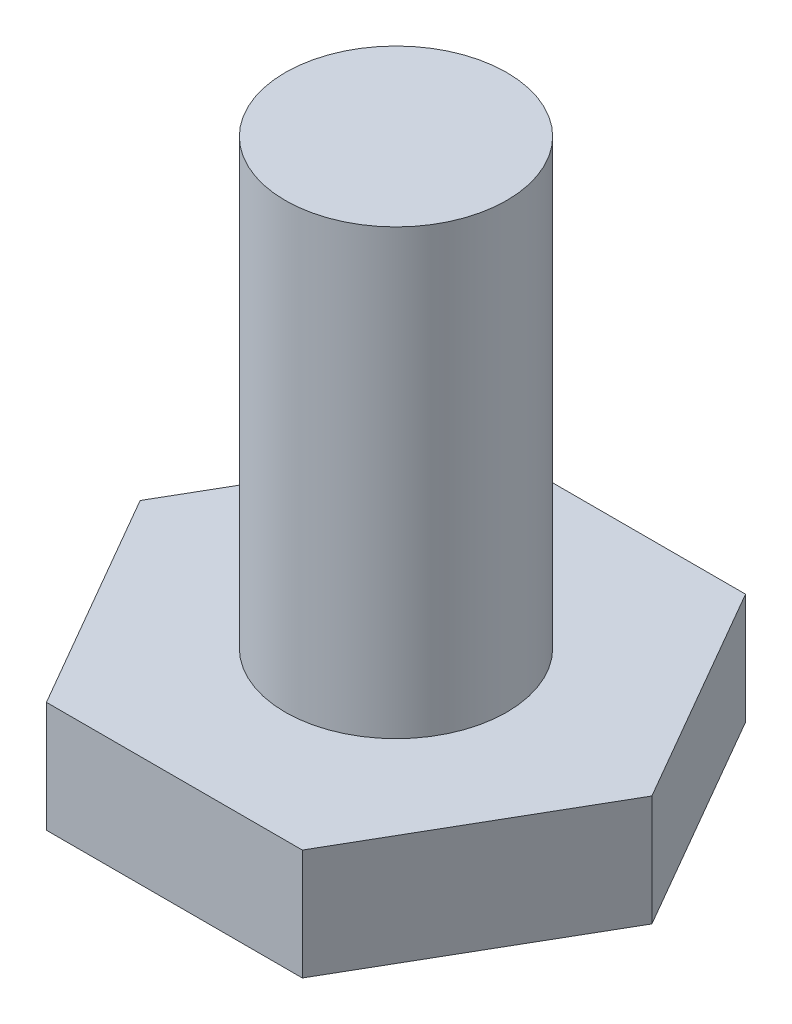
SolidWorks part; units mm, degrees
ref_plane "Front Plane" through (0, 0, 0) normal (0, 0, 1) x (1, 0, 0)
ref_plane "Top Plane" through (0, 0, 0) normal (0, 1, 0) x (1, 0, 0)
ref_plane "Right Plane" through (0, 0, 0) normal (1, 0, 0) x (0, 0, -1)
sketch "Sketch1" plane through (0, 0, 0) normal (0, 1, 0) x (1, 0, 0)
  line L1 (-2.3094, 4) -> (-4.6188, 0)
  line L2 (-4.6188, 0) -> (-2.3094, -4)
  line L3 (-2.3094, -4) -> (2.3094, -4)
  line L4 (2.3094, -4) -> (4.6188, 0)
  line L5 (4.6188, 0) -> (2.3094, 4)
  line L6 (2.3094, 4) -> (-2.3094, 4)
  circle A0 centre (0, 0) radius 4 construction
  dimension "D1" = 8
extrude "Boss-Extrude1" add sketch "Sketch1" along normal blind 2
sketch "Sketch2" plane through (0, 0, 0) normal (0, 1, 0) x (1, 0, 0)
  circle A0 centre (0, 0) radius 2
  dimension "D1" = 4
extrude "Boss-Extrude2" add sketch "Sketch2" along normal blind 10
thread "Thread1" pitch 0.7 start angle 0, offset 0, length 0, pitch 0.7, diameter 4
ref_plane "Plane1" through (-2, 10, 0) normal (0, 0, 1) x (-1, 0, 0)
sketch "Thread Profile1" plane through (-2, 10, 0) normal (0, 0, 1) x (-1, 0, 0)
  line L0 (0, 0) -> (0, 0.7) construction
  line L11 (0, 0) -> (0, 0.6125)
  line L12 (0, 0.6125) -> (-0.3789, 0.3937)
  line L13 (-0.3789, 0.3937) -> (-0.3789, 0.2187)
  line L15 (-0.3789, 0.2187) -> (0, 0)
  line L17 (-0.3789, 0.3062) -> (0, 0.3062) construction
  point P2 (0, 0)
  dimension "Pitch" = 0.7
  dimension "Profile_Angle" = 60
  dimension "Profile_Land" = 0.175
  dimension "Profile_Height" = 0.3789
